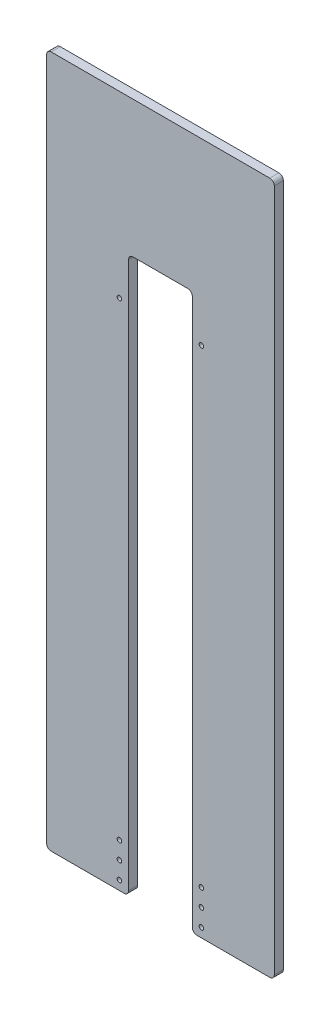
SolidWorks part; units mm, degrees
ref_plane "Front Plane" through (0, 0, 0) normal (0, 0, 1) x (1, 0, 0)
ref_plane "Top Plane" through (0, 0, 0) normal (0, 1, 0) x (1, 0, 0)
ref_plane "Right Plane" through (0, 0, 0) normal (1, 0, 0) x (0, 0, -1)
sketch "Sketch1" plane through (0, 0, 0) normal (0, 0, 1) x (1, 0, 0)
  line L1 (-120, -760) -> (-200, -760)
  line L2 (45, -755) -> (45, -5)
  line L3 (40, 0) -> (-200, 0)
  line L4 (-205, -755) -> (-205, -5)
  line L5 (40, -760) -> (-40, -760)
  line L6 (-45, -755) -> (-45, -155)
  line L7 (-50, -150) -> (-110, -150)
  line L8 (-115, -755) -> (-115, -155)
  line L9 (-115, 0) -> (-115, -760) construction
  line L10 (-45, -760) -> (-45, 0) construction
  arc A0 (45, -5) -> (40, 0) centre (40, -5) ccw
  arc A1 (-200, 0) -> (-205, -5) centre (-200, -5) ccw
  arc A2 (-200, -760) -> (-205, -755) centre (-200, -755) cw
  arc A3 (40, -760) -> (45, -755) centre (40, -755) ccw
  arc A4 (-45, -155) -> (-50, -150) centre (-50, -155) ccw
  arc A5 (-110, -150) -> (-115, -155) centre (-110, -155) ccw
  arc A6 (-115, -755) -> (-120, -760) centre (-120, -755) cw
  arc A7 (-45, -755) -> (-40, -760) centre (-40, -755) ccw
  point P10 (-205, 0)
  point P15 (45, -760)
  point P28 (-115, -150)
  point P30 (-45, -760)
  dimension "D1" = 5
  dimension "D2" = 5
  dimension "D3" = 5
  dimension "D4" = 150
extrude "Boss-Extrude1" add sketch "Sketch1" along normal blind 10
hole_wizard "M6 Tapped Hole" positions "Sketch2" profile "Sketch3" tap size "M6" standard "ISO" end condition through all
sketch "Sketch2" plane through (479.8458, 700.8861, 20) normal (0, 0, 1) x (-1, 0, 0)
  point P0 (514.8458, 897.4716)
  point P3 (537.8458, 897.4716)
  point P6 (581.8458, 897.4716)
  point P9 (604.8458, 897.4716)
  point P12 (514.8458, 1450.8861)
  point P15 (514.8458, 1412.8861)
  point P18 (537.8458, 1453.8861)
  point P21 (537.8458, 1409.8861)
  point P24 (581.8458, 1453.8861)
  point P27 (581.8458, 1409.8861)
  point P30 (604.8458, 1450.8861)
  point P33 (604.8458, 1412.8861)
  point P36 (514.8458, 1431.8861)
  point P39 (537.8458, 1431.8861)
  point P43 (581.8458, 1431.8861)
  point P46 (604.8458, 1431.8861)
sketch "Sketch3" plane through (-35, -196.5855, 20) normal (1, 0, 0) x (0, -1, 0)
  line L0 (0, 0) -> (0, 20)
  line L1 (0, 20) -> (2.5, 20)
  line L2 (2.5, 20) -> (2.5, 0)
  line L3 (2.5, 0) -> (0, 0)
  line L4 (0, -6.35) -> (0, 107.95) construction
  dimension "Thread Major Dia." = 5
  dimension "Thru Tap Drill Depth" = 20
